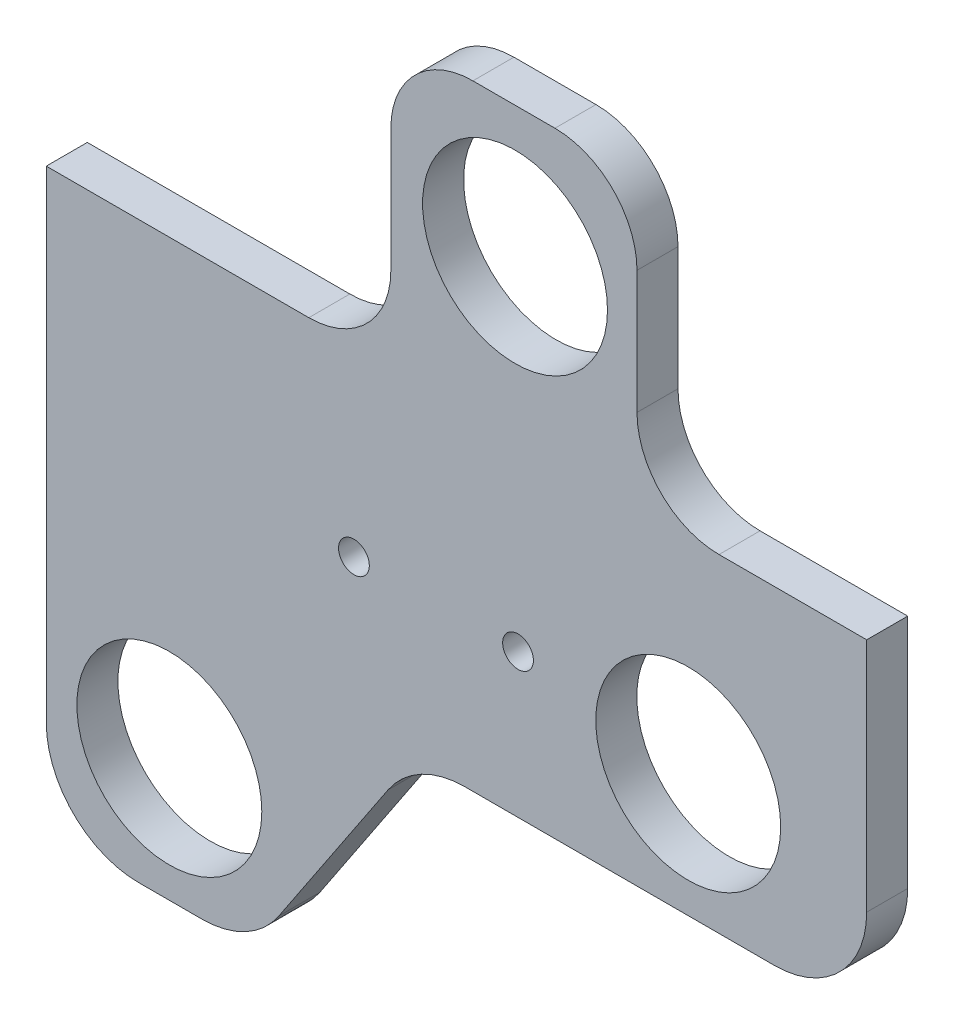
SolidWorks part; units mm, degrees
material "6063-T1"
ref_plane "Front Plane" through (0, 0, 0) normal (0, 0, 1) x (1, 0, 0)
ref_plane "Top Plane" through (0, 0, 0) normal (0, 1, 0) x (1, 0, 0)
ref_plane "Right Plane" through (0, 0, 0) normal (1, 0, 0) x (0, 0, -1)
sketch "Sketch1" plane through (0, 0, 0) normal (0, 0, 1) x (1, 0, 0)
  line L0 (63.5, -6.35) -> (-6.35, -6.35)
  line L1 (-63.5, 44.45) -> (63.5, 44.45)
  line L2 (-63.5, 44.45) -> (-63.5, -44.45)
  line L3 (-63.5, -44.45) -> (63.5, -44.45)
  line L4 (63.5, 44.45) -> (63.5, -44.45)
  line L5 (-63.5, 44.45) -> (63.5, -44.45) construction
  line L6 (-63.5, -44.45) -> (63.5, 44.45) construction
  line L7 (-6.35, -6.35) -> (-31.75, -44.45)
  circle A0 centre (-44.45, -25.4) radius 14.3129
  circle A1 centre (35.8719, 12.7) radius 14.3129
  point P0 (0, 0)
  dimension "D1" = 28.6258
  dimension "D2" = 28.6258
  dimension "D3" = 88.9
  dimension "D4" = 19.05
  dimension "D5" = 57.15
  dimension "D6" = 88.9
  dimension "D7" = 19.05
  dimension "D8" = 127
  dimension "D9" = 38.1
  dimension "D10" = 31.75
  dimension "D11" = 57.15
extrude "Boss-Extrude1" add sketch "Sketch1" along normal blind 6.35 contours L7 L0 L4 L1 L2 L3 A1 A0
fillet "Fillet1" radius 14.2875 4 edges at (63.5, -6.35, 3.175) (-6.35, -6.35, 3.175) (-31.75, -44.45, 3.175) (-63.5, -44.45, 3.175)
sketch "Sketch2" plane through (0, 0, 6.35) normal (0, 0, 1) x (1, 0, 0)
  line L0 (-63.5, 44.45) -> (63.5, 44.45) construction
  line L1 (-10.16, 44.45) -> (27.94, 44.45)
  line L2 (-10.16, 44.45) -> (-10.16, 88.9)
  line L3 (-10.16, 88.9) -> (27.94, 88.9)
  line L4 (27.94, 44.45) -> (27.94, 88.9)
  line L5 (-63.5, 44.45) -> (-63.5, -30.1625) construction
  dimension "D1" = 44.45
  dimension "D2" = 53.34
  dimension "D3" = 38.1
extrude "Boss-Extrude2" add sketch "Sketch2" against normal blind 6.35
sketch "Sketch3" plane through (0, 0, 6.35) normal (0, 0, 1) x (1, 0, 0)
  circle A0 centre (9.063, 68.5776) radius 14.3129
  circle A3 centre (35.8719, 12.7) radius 14.3129 construction
  dimension "D1" = 28.6258
  dimension "D2" = 61.976
extrude "Cut-Extrude1" cut sketch "Sketch3" against normal through all
sketch "Sketch4" plane through (0, 0, 6.35) normal (0, 0, 1) x (1, 0, 0)
  circle A0 centre (-16.337, 68.5776) radius 2.3813
  circle A1 centre (34.463, 68.5776) radius 2.3812
  circle A2 centre (9.063, 68.5776) radius 14.2875
  circle A3 centre (9.063, 68.5776) radius 25.4 construction
  dimension "D1" = 50.8
  dimension "D2" = 4.7625
  dimension "D3" = 4.7625
extrude "Cut-Extrude2" [suppressed] cut sketch "Sketch4" against normal through all
sketch "Sketch5" plane through (0, 0, 6.35) normal (0, 0, 1) x (1, 0, 0)
  circle A0 centre (-15.875, 15.875) radius 2.3813
  circle A1 centre (9.525, 15.875) radius 2.3813
  dimension "D1" = 4.7625
  dimension "D2" = 4.7625
  dimension "D3" = 25.4
  dimension "D4" = 15.875
  dimension "D5" = 9.525
extrude "Cut-Extrude3" cut sketch "Sketch5" against normal through all
fillet "Fillet2" radius 12.7 4 edges at (-10.16, 88.9, 3.175) (27.94, 88.9, 3.175) (27.94, 44.45, 3.175) (-10.16, 44.45, 3.175)
